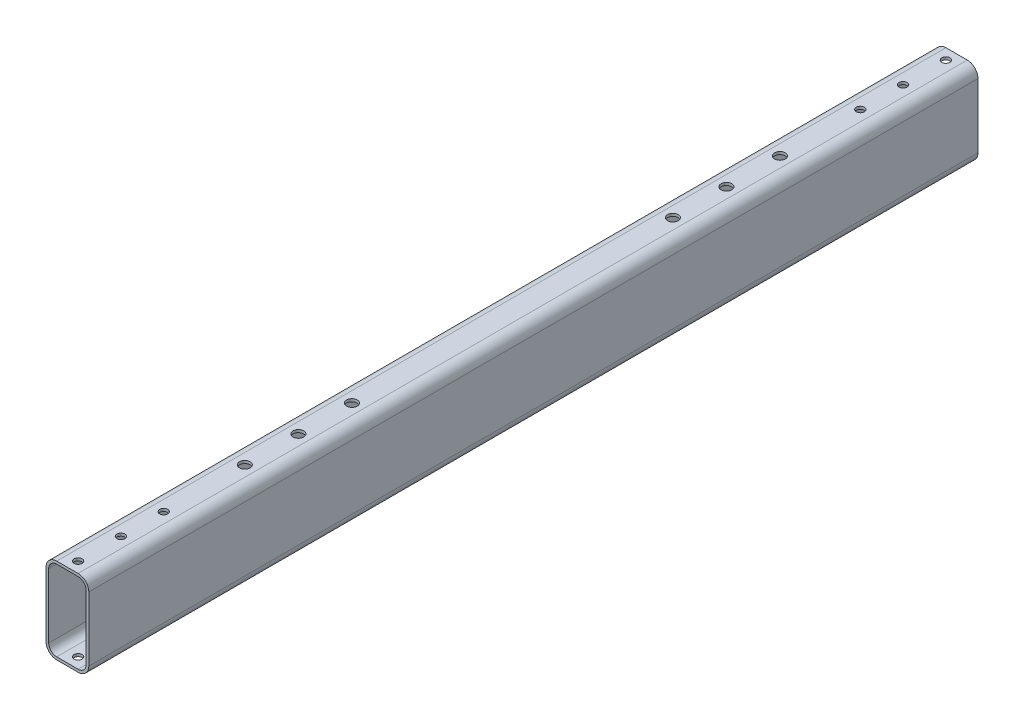
SolidWorks part; units mm, degrees
material "6061-T6 (SS)"
ref_plane "Front Plane" through (0, 0, 0) normal (0, 0, 1) x (1, 0, 0)
ref_plane "Top Plane" through (0, 0, 0) normal (0, 1, 0) x (1, 0, 0)
ref_plane "Right Plane" through (0, 0, 0) normal (1, 0, 0) x (0, 0, -1)
sketch "Sketch1" plane through (0, 0, 0) normal (0, 0, 1) x (1, 0, 0)
  line L1 (-6.35, -25.4) -> (6.35, -25.4)
  line L2 (-12.7, -19.05) -> (-12.7, 19.05)
  line L3 (-6.35, 25.4) -> (6.35, 25.4)
  line L4 (12.7, -19.05) -> (12.7, 19.05)
  line L5 (-12.7, -25.4) -> (12.7, 25.4) construction
  line L6 (-12.7, 25.4) -> (12.7, -25.4) construction
  arc A0 (-12.7, -19.05) -> (-6.35, -25.4) centre (-6.35, -19.05) ccw
  arc A1 (6.35, -25.4) -> (12.7, -19.05) centre (6.35, -19.05) ccw
  arc A2 (6.35, 25.4) -> (12.7, 19.05) centre (6.35, 19.05) cw
  arc A3 (-12.7, 19.05) -> (-6.35, 25.4) centre (-6.35, 19.05) cw
  point P0 (0, 0)
  dimension "D3" = 6.35
  dimension "D1" = 50.8
  dimension "D2" = 25.4
extrude "Extrude-Thin1" add sketch "Sketch1" along normal blind 527.685 thin thin type one direction reverse wall 1.5875
hole_wizard "3/16 (0.1875) Diameter Hole1" positions "3DSketch1" profile "Sketch3" hole size "3/16" standard "ANSI Inch" end condition through all
sketch3d "3DSketch1"
  line L1 (6.35, 25.4, 0) -> (-6.35, 25.4, 0) construction
  line L6 (0, 25.4, 527.685) -> (0, 25.4, 0) construction
  line L7 (6.35, 25.4, 527.685) -> (-6.35, 25.4, 527.685) construction
  point P57 (0, 25.4, 6.35)
  point P59 (0, 25.4, 31.75)
  point P61 (0, 25.4, 57.15)
  point P63 (0, 25.4, 495.935)
  point P65 (0, 25.4, 470.535)
  point P67 (0, 25.4, 521.335)
  dimension "D1" = 25.4
  dimension "D2" = 25.4
  dimension "D3" = 6.35
  dimension "D4" = 25.4
  dimension "D5" = 25.4
  dimension "D6" = 6.35
sketch "Sketch3" plane through (0, 25.4, 521.335) normal (1, 0, 0) x (0, 0, 1)
  line L0 (0, 0) -> (0, 50.8)
  line L1 (0, 50.8) -> (2.3812, 50.8)
  line L2 (2.3812, 50.8) -> (2.3812, 0)
  line L5 (2.3812, 0) -> (0, 0)
  line L11 (0, -6.35) -> (0, 107.95) construction
  dimension "Thru Hole Dia." = 4.7625
  dimension "Thru Hole Depth" = 50.8
hole_wizard "3/16 (0.195) Diameter Hole1" positions "Sketch4" profile "Sketch5" hole size "3/16" standard "ANSI Inch"
sketch "Sketch4" plane through (0, -25.4, 0) normal (0, -1, 0) x (-1, 0, 0)
  point P3 (3.175, -115.4797)
  point P6 (-3.175, -140.8797)
  point P9 (3.175, -166.2797)
  point P12 (-3.175, -191.6797)
  point P15 (-3.175, -344.0797)
  point P18 (3.175, -369.4797)
  point P21 (-3.175, -394.8797)
  point P24 (3.175, -420.2797)
sketch "Sketch5" plane through (-3.175, -25.4, 115.4797) normal (1, 0, 0) x (0, 0, -1)
  line L0 (0, 0) -> (0, 1.5875)
  line L1 (0, 1.5875) -> (2.4765, 1.5875)
  line L2 (2.4765, 1.5875) -> (2.4765, 0)
  line L5 (2.4765, 0) -> (0, 0)
  line L11 (0, -6.35) -> (0, 107.95) construction
  dimension "Thru Hole Dia." = 4.953
  dimension "Thru Hole Depth" = 1.5875
hole_wizard "1/4 (0.25) Diameter Hole1" positions "Sketch7" profile "Sketch6" hole size "1/4" standard "ANSI Inch"
sketch "Sketch7" plane through (0, 25.4, 0) normal (0, 1, 0) x (1, 0, 0)
  point P0 (0, -104.85)
  point P3 (0, -136.6)
  point P6 (0, -168.35)
  point P9 (0, -422.3748)
  point P12 (0, -390.6248)
  point P15 (0, -358.8748)
sketch "Sketch6" plane through (0, 25.4, 104.85) normal (1, 0, 0) x (0, 0, 1)
  line L0 (0, 0) -> (0, 27.3077)
  line L1 (0, 27.3077) -> (3.175, 25.4)
  line L2 (3.175, 25.4) -> (3.175, 0)
  line L5 (3.175, 0) -> (0, 0)
  line L10 (0, 27.3077) -> (-3.175, 25.4) construction
  line L11 (0, -6.35) -> (0, 107.95) construction
  dimension "Hole Dia." = 6.35
  dimension "Hole Depth" = 25.4
  dimension "Drill Angle" = 118
